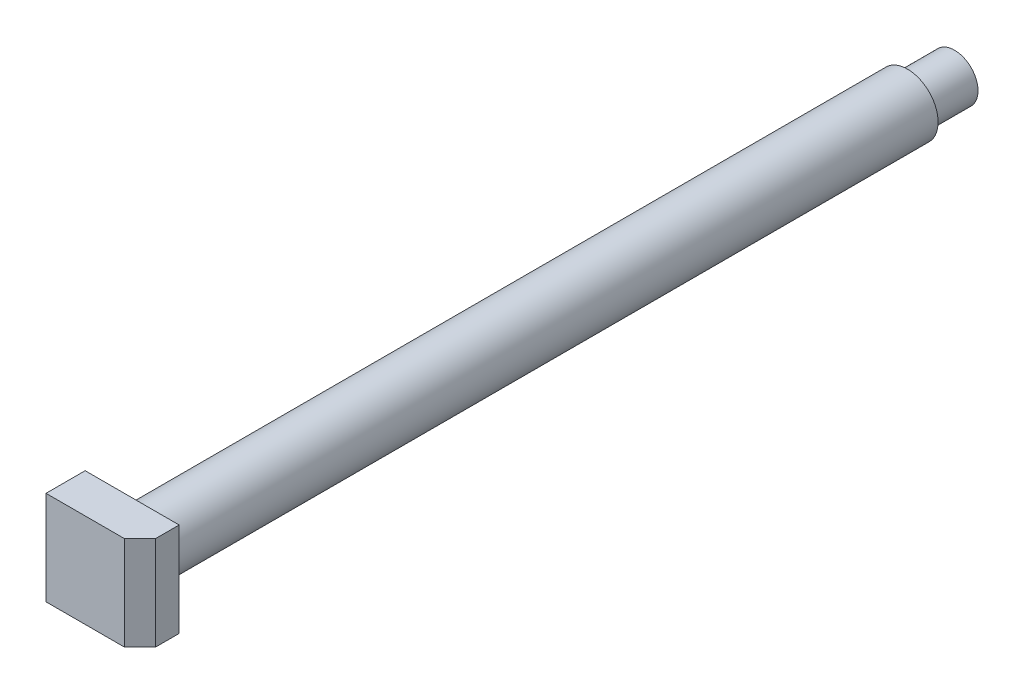
SolidWorks part; units mm, degrees
ref_plane "Plan de face" through (0, 0, 0) normal (0, 0, 1) x (1, 0, 0)
ref_plane "Plan de dessus" through (0, 0, 0) normal (0, 1, 0) x (1, 0, 0)
ref_plane "Plan de droite" through (0, 0, 0) normal (1, 0, 0) x (0, 0, -1)
sketch "Esquisse1" plane through (0, 0, 0) normal (0, 0, 1) x (1, 0, 0)
  circle A0 centre (-68.2757, -15.5806) radius 3.9
  dimension "D1" = 7.8
extrude "Boss.-Extru.1" add sketch "Esquisse1" along normal blind 105
sketch "Esquisse2" plane through (0, 0, 105) normal (0, 0, 1) x (1, 0, 0)
  line L1 (-74.2757, -21.5806) -> (-62.2757, -21.5806)
  line L2 (-74.2757, -21.5806) -> (-74.2757, -9.5806)
  line L3 (-74.2757, -9.5806) -> (-62.2757, -9.5806)
  line L4 (-62.2757, -21.5806) -> (-62.2757, -9.5806)
  line L5 (-74.2757, -21.5806) -> (-62.2757, -9.5806) construction
  line L6 (-74.2757, -9.5806) -> (-62.2757, -21.5806) construction
  circle A0 centre (-68.2757, -15.5806) radius 3.9 construction
  point P0 (-68.2757, -15.5806)
  dimension "D1" = 12
extrude "Boss.-Extru.2" add sketch "Esquisse2" along normal blind 5
sketch "Esquisse14" plane through (0, 0, 0) normal (0, 0, -1) x (-1, 0, 0)
  circle A0 centre (68.2757, -15.5806) radius 3
  circle A1 centre (68.2757, -15.5806) radius 3.9 construction
  circle A2 centre (68.2757, -15.5806) radius 3.9
  dimension "D1" = 6
extrude "Enlèv. mat.-Extru.1" cut sketch "Esquisse14" against normal blind 6
chamfer "Chanfrein1" distance 2 angle 45 1 edges at (-62.2757, -15.5806, 110)
hole_wizard "Trou pour taraudage pour trou taraudé M3x0.51" positions "Esquisse20" profile "Esquisse21" hole size "M3x0.5" standard "Ansi Metric"
sketch "Esquisse20" plane through (0, 0, 0) normal (0, 0, -1) x (-1, 0, 0)
  point P0 (68.2757, -15.5806)
sketch "Esquisse21" plane through (-68.2757, -15.5806, 0) normal (1, 0, 0) x (0, 1, 0)
  line L0 (0, 0) -> (0, 12)
  line L1 (0, 12) -> (1.25, 12)
  line L2 (1.25, 12) -> (1.25, 0)
  line L5 (1.25, 0) -> (0, 0)
  line L10 (0, 12) -> (-1.25, 12) construction
  line L11 (0, -6.35) -> (0, 107.95) construction
  dimension "Diamètre du perçage" = 2.5
  dimension "Profondeur du perçage" = 12
  dimension "Angle de pointe" = 180
